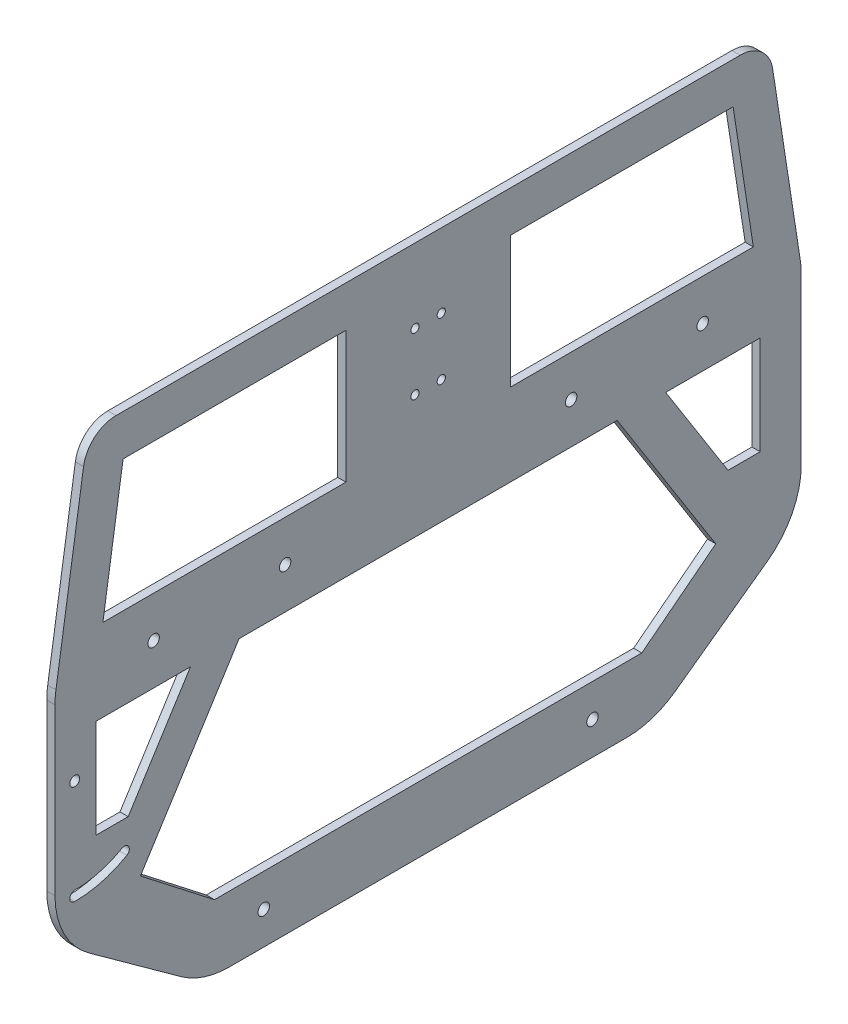
SolidWorks part; units mm, degrees
ref_plane "前视基准面" through (0, 0, 0) normal (0, 0, 1) x (1, 0, 0)
ref_plane "上视基准面" through (0, 0, 0) normal (0, 1, 0) x (1, 0, 0)
ref_plane "右视基准面" through (0, 0, 0) normal (1, 0, 0) x (0, 0, -1)
ref_plane "基准面1" through (4.7625, 0, 0) normal (1, 0, 0) x (0, 0, -1)
sketch "草图1" plane through (4.7625, 0, 0) normal (1, 0, 0) x (0, 0, -1)
  line L0 (-227, 0) -> (-227, -130)
  line L1 (-227, -130) -> (-137, -195)
  line L2 (-137, -195) -> (137, -195)
  line L3 (227, -130) -> (227, 0)
  line L4 (130, -155) -> (-130, -155)
  line L5 (-130, -155) -> (-175, -120)
  line L6 (-215, -50) -> (-215, -78.3993) construction
  line L7 (-215, -50) -> (-203.4472, -70.0101) construction
  line L8 (-207, 130) -> (207, 130)
  line L9 (-245.8641, 0) -> (287.7196, 0) construction
  line L11 (-207, 130) -> (-227, 0)
  line L12 (207, 130) -> (227, 0)
  line L13 (137, -195) -> (227, -130)
  line L15 (-115, -25) -> (115, -25)
  line L16 (-115, -25) -> (-175, -120)
  line L17 (115, -25) -> (175, -120)
  line L18 (130, -155) -> (175, -120)
  line L19 (0, 148.6831) -> (0, -319.0988) construction
  line L20 (-144.5687, -25) -> (-202, -25)
  line L21 (-202, -25) -> (-202, -85)
  line L22 (-202, -85) -> (-182.4634, -85)
  line L23 (-182.4634, -85) -> (-144.5687, -25)
  line L24 (182.4634, -85) -> (144.5687, -25)
  line L25 (202, -85) -> (182.4634, -85)
  line L26 (202, -25) -> (202, -85)
  line L27 (144.5687, -25) -> (202, -25)
  line L28 (0, 85) -> (-8, 85) construction
  line L29 (-8, 85) -> (-8, 50) construction
  line L30 (-8, 50) -> (0, 50) construction
  line L31 (-185.552, 105) -> (-50, 105)
  line L36 (-50, 105) -> (-50, 25)
  line L37 (-50, 25) -> (-197.8597, 25)
  line L38 (-197.8597, 25) -> (-185.552, 105)
  line L39 (50, 105) -> (50, 25)
  line L40 (50, 25) -> (197.8597, 25)
  line L41 (197.8597, 25) -> (185.552, 105)
  line L42 (185.552, 105) -> (50, 105)
  line L43 (-185.552, -175) -> (202, -175) construction
  circle A2 centre (-8, 85) radius 2.5
  circle A12 centre (-8, 50) radius 2.5
  circle A13 centre (8, 50) radius 2.5
  circle A14 centre (8, 85) radius 2.5
  circle A16 centre (-100, -175) radius 3.5
  circle A17 centre (100, -175) radius 3.5
  circle A38 centre (167, 0) radius 3.5
  circle A39 centre (87, 0) radius 3.5
  circle A40 centre (-87, 0) radius 3.5
  circle A41 centre (-167, 0) radius 3.5
  arc A42 (-215, -113.5) -> (-215, -107.5) centre (-215, -110.5) cw
  arc A43 (-215, -107.5) -> (-186.25, -99.7965) centre (-215, -50) ccw
  arc A44 (-186.25, -99.7965) -> (-183.25, -104.9926) centre (-184.75, -102.3945) cw
  arc A45 (-183.25, -104.9926) -> (-215, -113.5) centre (-215, -50) cw
  circle A46 centre (-215, -50) radius 3
  dimension "D1" = 7
  dimension "D2" = 7
  dimension "D3" = 7
  dimension "D4" = 7
  dimension "D6" = 0
  dimension "D7" = 60
  dimension "D30" = 57.5
  dimension "D31" = 63.5
  dimension "D32" = 6
  dimension "D43" = 5
  dimension "D44" = 5
  dimension "D49" = 20
  dimension "D50" = 100
  dimension "D52" = 7
  dimension "D53" = 7
  dimension "D5" = 130
  dimension "D8" = 60
  dimension "D9" = 20
  dimension "D10" = 20
  dimension "D11" = 87
  dimension "D12" = 87
  dimension "D13" = 80
  dimension "D14" = 80
  dimension "D15" = 25
  dimension "D16" = 130
  dimension "D17" = 115
  dimension "D18" = 115
  dimension "D19" = 350
  dimension "D20" = 95
  dimension "D21" = 65
  dimension "D22" = 274
  dimension "D23" = 35
  dimension "D24" = 60
  dimension "D25" = 95
  dimension "D26" = 130
  dimension "D27" = 130
  dimension "D28" = 90
  dimension "D29" = 65
  dimension "D33" = 40
  dimension "D34" = 70
  dimension "D35" = 30
  dimension "D36" = 120
  dimension "D37" = 25
  dimension "D38" = 25
  dimension "D39" = 60
  dimension "D40" = 8
  dimension "D41" = 35
  dimension "D42" = 50
  dimension "D45" = 25
  dimension "D46" = 25
  dimension "D47" = 25
  dimension "D48" = 50
  dimension "D51" = 100
extrude "凸台-拉伸1" add sketch "草图1" against normal blind 5
fillet "圆角1" radius 20 1 edges at (2.2625, 130, 207)
fillet "圆角2" radius 20 1 edges at (2.2625, 130, -207)
fillet "圆角3" radius 50 1 edges at (2.2625, 0, 227)
fillet "圆角4" radius 50 1 edges at (2.2625, 0, -227)
fillet "圆角5" radius 50 1 edges at (2.2625, -130, 227)
fillet "圆角6" radius 50 1 edges at (2.2625, -195, 137)
fillet "圆角7" radius 50 1 edges at (2.2625, -195, -137)
fillet "圆角8" radius 50 1 edges at (2.2625, -130, -227)
